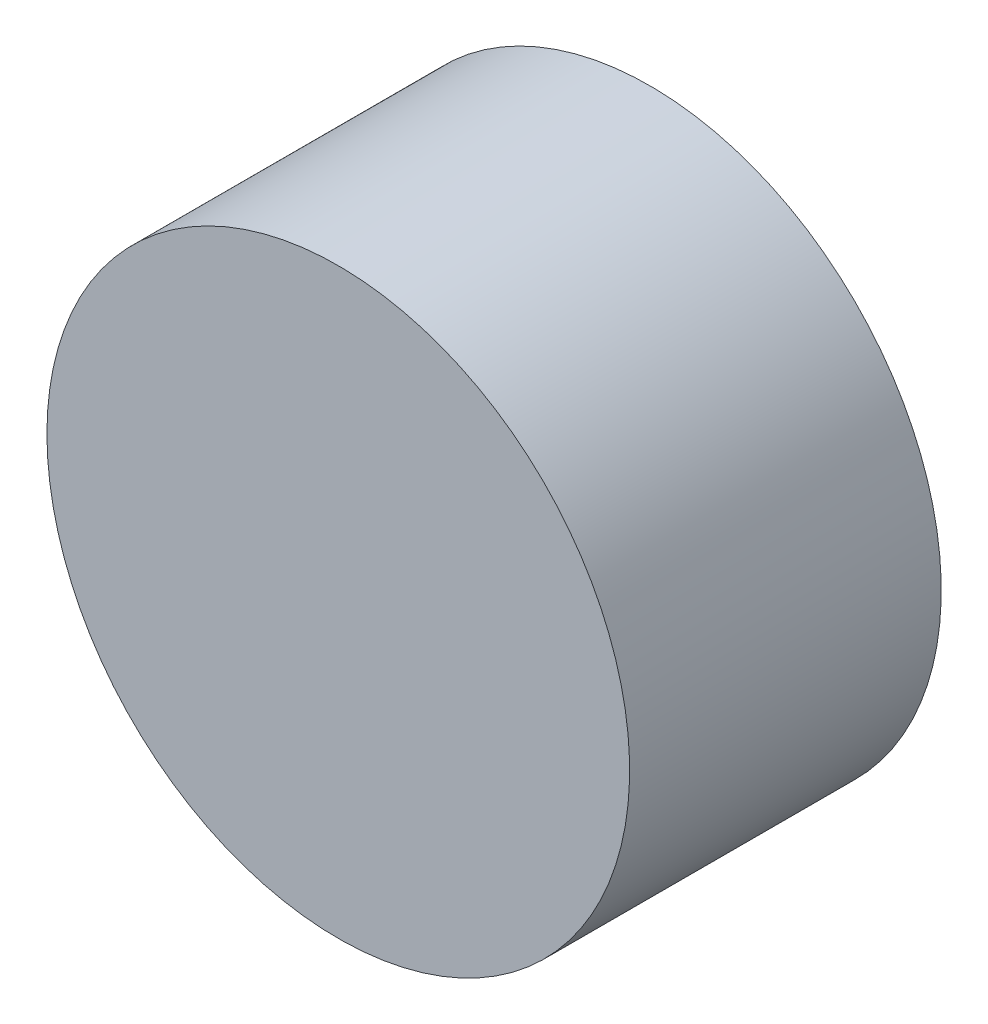
SolidWorks part; units mm, degrees
ref_plane "Front Plane" through (0, 0, 0) normal (0, 0, 1) x (1, 0, 0)
ref_plane "Top Plane" through (0, 0, 0) normal (0, 1, 0) x (1, 0, 0)
ref_plane "Right Plane" through (0, 0, 0) normal (1, 0, 0) x (0, 0, -1)
sketch "Sketch2" plane through (0, 0, 0) normal (0, 0, 1) x (1, 0, 0)
  circle A0 centre (0, 0) radius 42.075
  dimension "D1" = 84.15
extrude "Boss-Extrude1" add sketch "Sketch2" along normal blind 45
